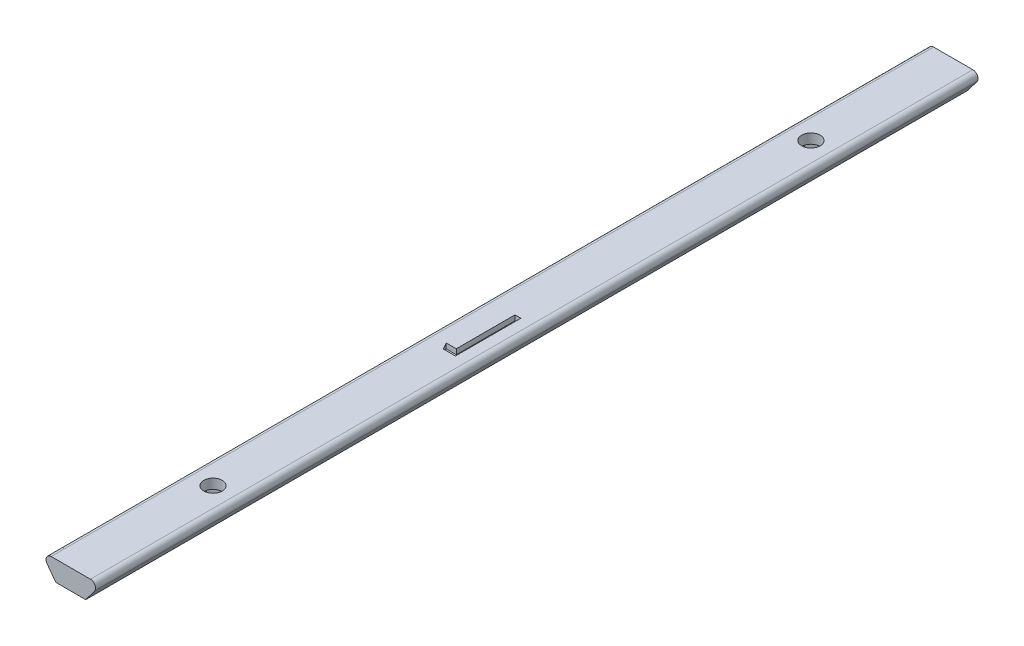
SolidWorks part; units mm, degrees
ref_plane "Front Plane" through (0, 0, 0) normal (0, 0, 1) x (1, 0, 0)
ref_plane "Top Plane" through (0, 0, 0) normal (0, 1, 0) x (1, 0, 0)
ref_plane "Right Plane" through (0, 0, 0) normal (1, 0, 0) x (0, 0, -1)
sketch "Sketch1" plane through (0, 0, 0) normal (0, 0, 1) x (1, 0, 0)
  line L0 (0, 0) -> (5.8, 0)
  line L1 (-2.9, 3.9) -> (8.7, 3.9)
  line L2 (0, 0) -> (-2.9, 3.9)
  line L3 (5.8, 0) -> (8.7, 3.9)
  dimension "D1" = 11.6
  dimension "D2" = 3.9
  dimension "D3" = 5.8
  dimension "D4" = 2.9
extrude "Boss-Extrude1" add sketch "Sketch1" along normal blind 171.2
fillet "Fillet1" radius 1 2 edges at (-2.9, 3.9, 85.6) (8.7, 3.9, 85.6)
sketch "Sketch2" plane through (0, 0, 0) normal (0, -1, 0) x (1, 0, 0)
  line L0 (2.9, 171.2) -> (2.9, 143.6) construction
  line L1 (0, 171.2) -> (5.8, 171.2) construction
  circle A0 centre (2.9, 143.6) radius 1.8
  dimension "D2" = 3.6
  dimension "D1" = 27.6
extrude "Cut-Extrude1" cut sketch "Sketch2" against normal blind 200
sketch "Sketch3" plane through (0, 0, 0) normal (0, -1, 0) x (1, 0, 0)
  line L1 (2.9287, 146.9485) -> (0.0145, 145.2991)
  line L2 (0.0145, 145.2991) -> (-0.0143, 141.9506)
  line L3 (-0.0143, 141.9506) -> (2.8713, 140.2515)
  line L4 (2.8713, 140.2515) -> (5.7855, 141.9009)
  line L5 (5.7855, 141.9009) -> (5.8143, 145.2494)
  line L6 (5.8143, 145.2494) -> (2.9287, 146.9485)
  circle A0 centre (2.9, 143.6) radius 2.9 construction
  dimension "D1" = 5.8
extrude "Cut-Extrude2" cut sketch "Sketch3" against normal blind 2
pattern_linear "LPattern1" count 3 spacing 116 along (0, 0, -1) of "Cut-Extrude1", "Cut-Extrude2"
sketch "Sketch4" plane through (0, 3.9, 0) normal (0, 1, 0) x (1, 0, 0)
  line L0 (-0.9102, -85.6) -> (0.0898, -85.6) construction
  line L3 (-0.9102, 0) -> (-0.9102, -171.2) construction
  text T0 "1" font "Century Gothic" height in points 48
  dimension "D1" = 1
extrude "Cut-Extrude3" cut sketch "Sketch4" against normal blind 1
